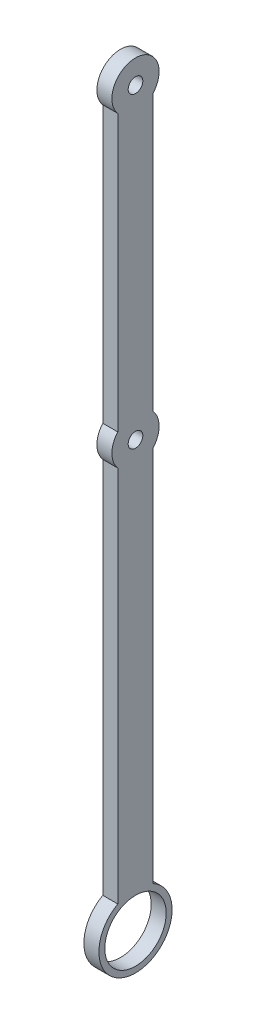
SolidWorks part; units mm, degrees
ref_plane "Front Plane" through (0, 0, 0) normal (0, 0, 1) x (1, 0, 0)
ref_plane "Top Plane" through (0, 0, 0) normal (0, 1, 0) x (1, 0, 0)
ref_plane "Right Plane" through (0, 0, 0) normal (1, 0, 0) x (0, 0, -1)
sketch "Sketch1" plane through (0, 0, 0) normal (1, 0, 0) x (0, 0, -1)
  line L0 (0, 0) -> (-3.75, -3.3072) construction
  line L2 (3.75, -3.3072) -> (3.75, -61.6928)
  line L3 (3.75, -61.6928) -> (-3.75, -61.6928) construction
  line L4 (-3.75, -3.3072) -> (-3.75, -61.6928)
  line L5 (3.75, -3.3072) -> (-3.75, -3.3072) construction
  line L6 (0, 0) -> (3.75, -3.3072) construction
  line L8 (-3.75, -68.3072) -> (-3.75, -148.2177)
  line L9 (3.75, -68.3072) -> (3.75, -148.2177)
  line L11 (0, -65) -> (0, -155) construction
  line L13 (-3.75, -68.3072) -> (3.75, -68.3072) construction
  circle A0 centre (0, 0) radius 1.55
  arc A1 (3.75, -3.3072) -> (-3.75, -3.3072) centre (0, 0) ccw
  arc A2 (-3.75, -61.6928) -> (-3.75, -68.3072) centre (0, -65) ccw
  circle A3 centre (0, -65) radius 1.55
  arc A4 (-3.75, -148.2177) -> (3.75, -148.2177) centre (0, -155) ccw
  circle A5 centre (0, -155) radius 6.5
  arc A6 (3.75, -68.3072) -> (3.75, -61.6928) centre (0, -65) ccw
  dimension "D1" = 3.1
  dimension "D2" = 10
  dimension "D4" = 10
  dimension "D6" = 3.1
  dimension "D8" = 90
  dimension "D9" = 7.75
  dimension "D10" = 13
  dimension "D3" = 7.5
  dimension "D5" = 65
  dimension "D7" = 7.5
extrude "Boss-Extrude3" add sketch "Sketch1" along normal blind 3.175
